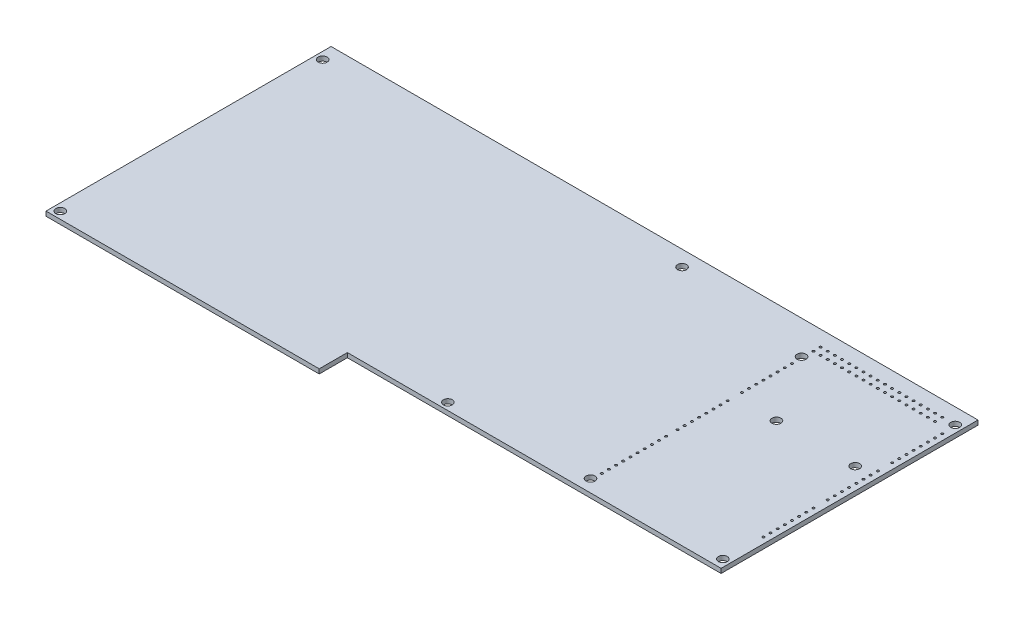
SolidWorks part; units mm, degrees
material "E-Glass Fiber"
ref_plane "Front Plane" through (0, 0, 0) normal (0, 0, 1) x (1, 0, 0)
ref_plane "Top Plane" through (0, 0, 0) normal (0, 1, 0) x (1, 0, 0)
ref_plane "Right Plane" through (0, 0, 0) normal (1, 0, 0) x (0, 0, -1)
sketch "Sketch1" plane through (0, 0, 0) normal (0, 1, 0) x (1, 0, 0)
  line L0 (-55, 0) -> (55, 0) construction
  line L1 (-0.4335, 10.8084) -> (-133.1733, 10.8084)
  line L2 (-0.4335, 10.8084) -> (-0.4335, 102.06)
  line L4 (-230.216, 0.8084) -> (-230.216, 102.06)
  line L5 (-230.216, 102.06) -> (-0.4335, 102.06)
  line L7 (-133.1733, 10.8084) -> (-133.1733, 0.8084)
  line L8 (-133.1733, 0.8084) -> (-230.216, 0.8084)
  circle A0 centre (-8.0535, 66.04) radius 1.5875
  circle A1 centre (-35.9935, 66.04) radius 1.5875
  circle A2 centre (-2.9735, 13.97) radius 1.5875
  circle A3 centre (-51.2335, 15.24) radius 1.5875
  circle A4 centre (-2.9735, 96.52) radius 1.5875
  circle A5 centre (-51.2335, 90.17) radius 1.5875
  circle A7 centre (-227.676, 3.3484) radius 1.5875
  circle A8 centre (-227.676, 96.52) radius 1.5875
  circle A9 centre (-100.0106, 96.52) radius 1.5875
  circle A10 centre (-100.0106, 13.3484) radius 1.5875
  dimension "D8" = 3.175
  dimension "D16" = 2.54
  dimension "D4" = 5.54
  dimension "D2" = 230
  dimension "D3" = 10
  dimension "D5" = 2.54
  dimension "D6" = 2.54
  dimension "D9" = 66.04
  dimension "D10" = 35.56
  dimension "D11" = 7.62
  dimension "D12" = 13.97
  dimension "D13" = 2.54
  dimension "D14" = 15.24
  dimension "D15" = 50.8
  dimension "D17" = 90.17
extrude "Boss-Extrude1" add sketch "Sketch1" against normal blind 1.6
sketch "Sketch2" plane through (0, 0, 0) normal (0, 1, 0) x (1, 0, 0)
  line L0 (0, -0.9075) -> (0, 0.9075) construction
  line L1 (-0.9075, 0) -> (0.9075, 0) construction
  circle A0 centre (-2.54, 27.94) radius 0.4
  dimension "D1" = 0.8
  dimension "D2" = 2.54
  dimension "D3" = 27.94
extrude "Cut-Extrude1" cut sketch "Sketch2" against normal blind 1.65
sketch "Sketch3" plane through (0, 0, 0) normal (0, 1, 0) x (1, 0, 0)
  line L0 (0, -0.9075) -> (0, 0.9075) construction
  line L1 (-0.9075, 0) -> (0.9075, 0) construction
  circle A0 centre (-50.8, 18.796) radius 0.4
  dimension "D2" = 0.8
  dimension "D1" = 50.8
  dimension "D3" = 18.796
extrude "Cut-Extrude2" cut sketch "Sketch3" against normal blind 1.65
pattern_linear "LPattern1" count 26 spacing 2.54 along (0, 0, -1) skipping (8, 0), (17, 0) of "Cut-Extrude1"
sketch "Sketch4" plane through (0, 0, 0) normal (0, 1, 0) x (1, 0, 0)
  line L0 (-0.9075, 0) -> (0.9075, 0) construction
  line L1 (0, -0.9075) -> (0, 0.9075) construction
  circle A0 centre (-50.8, 45.72) radius 0.4
  dimension "D3" = 0.8
  dimension "D1" = 45.72
  dimension "D2" = 50.8
extrude "Cut-Extrude3" cut sketch "Sketch4" against normal blind 1.65
pattern_linear "LPattern2" count 10 spacing 2.54 along (0, 0, -1) of "Cut-Extrude2"
pattern_linear "LPattern3" count 17 spacing 2.54 along (0, 0, -1) skipping (8, 0) of "Cut-Extrude3"
sketch "Sketch5" plane through (0, 0, 0) normal (0, 1, 0) x (1, 0, 0)
  line L0 (-27.89, 66.18) -> (-27.89, 63.64) construction
  line L1 (-30.43, 66.18) -> (-25.35, 66.18) construction
  line L2 (-30.43, 66.18) -> (-30.43, 63.64) construction
  line L3 (-30.43, 63.64) -> (-25.35, 63.64) construction
  line L4 (-25.35, 66.18) -> (-25.35, 63.64) construction
  line L5 (-0.9075, 0) -> (0.9075, 0) construction
  line L6 (0, -0.9075) -> (0, 0.9075) construction
  circle A0 centre (-30.43, 66.18) radius 0.4
  circle A1 centre (-27.89, 66.18) radius 0.4
  circle A2 centre (-25.35, 66.18) radius 0.4
  circle A3 centre (-25.35, 63.64) radius 0.4
  circle A4 centre (-27.89, 63.64) radius 0.4
  circle A5 centre (-30.43, 63.64) radius 0.4
  circle A6 centre (-47.498, 15.748) radius 0.4
  circle A7 centre (-47.498, 18.288) radius 0.4
  circle A8 centre (-47.498, 20.828) radius 0.4
  circle A9 centre (-44.958, 20.828) radius 0.4
  circle A10 centre (-44.958, 18.288) radius 0.4
  circle A11 centre (-44.958, 15.748) radius 0.4
  circle A12 centre (-42.418, 18.288) radius 0.4
  circle A13 centre (-42.418, 20.828) radius 0.4
  circle A14 centre (-39.878, 20.828) radius 0.4
  circle A15 centre (-39.878, 18.288) radius 0.4
  circle A16 centre (-26.035, 20.955) radius 0.5
  circle A17 centre (-26.035, 15.875) radius 0.5
  dimension "D4" = 0.8
  dimension "D14" = 1
  dimension "D1" = 2.54
  dimension "D2" = 2.54
  dimension "D3" = 2.54
  dimension "D5" = 63.64
  dimension "D6" = 30.43
  dimension "D7" = 2.54
  dimension "D8" = 2.54
  dimension "D9" = 2.54
  dimension "D10" = 2.54
  dimension "D11" = 2.54
  dimension "D12" = 47.498
  dimension "D13" = 15.748
  dimension "D15" = 5.08
  dimension "D16" = 15.875
  dimension "D17" = 26.035
extrude "Cut-Extrude4" [suppressed] cut sketch "Sketch5" against normal blind 10
sketch "Sketch6" plane through (0, 0, 0) normal (0, 1, 0) x (1, 0, 0)
  line L0 (0, -55) -> (0, 55) construction
  line L1 (-55, 0) -> (55, 0) construction
  line L2 (-20.193, 29.845) -> (-20.193, 32.385) construction
  circle A0 centre (-20.193, 29.845) radius 0.4
  circle A1 centre (-12.573, 29.845) radius 0.4
  circle A2 centre (-20.193, 32.385) radius 0.4
  circle A3 centre (-12.573, 32.385) radius 0.4
  circle A4 centre (-20.193, 34.925) radius 0.4
  circle A5 centre (-12.573, 34.925) radius 0.4
  circle A6 centre (-20.193, 37.465) radius 0.4
  circle A7 centre (-12.573, 37.465) radius 0.4
  circle A8 centre (-20.193, 40.005) radius 0.4
  circle A9 centre (-12.573, 40.005) radius 0.4
  circle A10 centre (-20.193, 42.545) radius 0.4
  circle A11 centre (-12.573, 42.545) radius 0.4
  circle A12 centre (-20.193, 45.085) radius 0.4
  circle A13 centre (-12.573, 45.085) radius 0.4
  circle A14 centre (-20.193, 47.625) radius 0.4
  circle A15 centre (-12.573, 47.625) radius 0.4
  circle A16 centre (-20.193, 50.165) radius 0.4
  circle A17 centre (-12.573, 50.165) radius 0.4
  circle A18 centre (-20.193, 52.705) radius 0.4
  circle A19 centre (-12.573, 52.705) radius 0.4
  circle A20 centre (-20.193, 55.245) radius 0.4
  circle A21 centre (-12.573, 55.245) radius 0.4
  circle A22 centre (-20.193, 57.785) radius 0.4
  circle A23 centre (-12.573, 57.785) radius 0.4
  circle A24 centre (-20.193, 60.325) radius 0.4
  circle A25 centre (-12.573, 60.325) radius 0.4
  circle A26 centre (-20.193, 62.865) radius 0.4
  circle A27 centre (-12.573, 62.865) radius 0.4
  dimension "D1" = 0.8
  dimension "D2" = 7.62
  dimension "D3" = 12.573
  dimension "D4" = 29.845
  dimension "D6" = 2.54
  dimension "D5" = 14
extrude "Cut-Extrude5" [suppressed] cut sketch "Sketch6" against normal blind 10
sketch "Sketch7" plane through (0, 0, 0) normal (0, 1, 0) x (1, 0, 0)
  line L0 (-55, 0) -> (55, 0) construction
  line L1 (0, -55) -> (0, 55) construction
  circle A0 centre (-50.8, 96.52) radius 0.4
  circle A1 centre (-50.8, 93.98) radius 0.4
  dimension "D1" = 0.8
  dimension "D2" = 2.54
  dimension "D3" = 96.52
  dimension "D4" = 50.8
extrude "Cut-Extrude6" cut sketch "Sketch7" against normal blind 10
pattern_linear "LPattern4" count 18 spacing 2.54 along (1, 0, 0) of "Cut-Extrude6"
equation "\"D13@Sketch5\"=0.001*25.4*620"
equation "\"D16@Sketch5\"=625*0.001*25.4"
equation "\"D17@Sketch5\"=1025*0.001*25.4"
